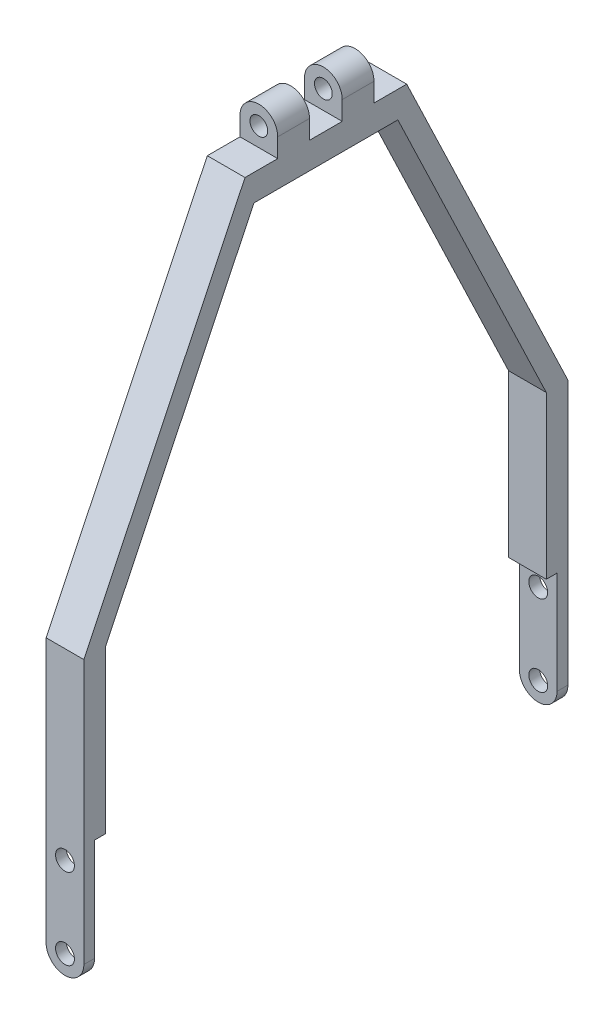
SolidWorks part; units mm, degrees
ref_plane "Front Plane" through (0, 0, 0) normal (0, 0, 1) x (1, 0, 0)
ref_plane "Top Plane" through (0, 0, 0) normal (0, 1, 0) x (1, 0, 0)
ref_plane "Right Plane" through (0, 0, 0) normal (1, 0, 0) x (0, 0, -1)
sketch "Croquis1" plane through (0, 0, 0) normal (0, 0, 1) x (1, 0, 0)
  line L10 (-3.5, 100) -> (-3.5, -15)
  line L11 (3.5, -15) -> (3.5, 100)
  circle A18 centre (0, 0) radius 1.75
  circle A19 centre (0, -15) radius 1.75
  arc A20 (-3.5, -15) -> (3.5, -15) centre (0, -15) ccw
  arc A22 (3.5, 100) -> (-3.5, 100) centre (0, 100) ccw
  circle A23 centre (0, 100) radius 1.65
  dimension "D3" = 3.5
  dimension "D4" = 7
  dimension "D6" = 7
  dimension "D7" = 3.3
  dimension "D2" = 3.5
  dimension "D1" = 15
  dimension "D5" = 100
extrude "Saliente-Extruir1" add sketch "Croquis1" against normal blind 89.8
sketch "Croquis2" plane through (3.5, 0, 0) normal (1, 0, 0) x (0, 0, -1)
  line L0 (0, -18.5) -> (89.8, -18.5) construction
  line L1 (2, -18.5) -> (87.8, -18.5)
  line L2 (2, -18.5) -> (2, 4)
  line L3 (2, 4) -> (87.8, 4)
  line L4 (87.8, -18.5) -> (87.8, 4)
  line L5 (89.8, -15) -> (89.8, 100) construction
  line L6 (29.9, 103.5) -> (0, 103.5)
  line L7 (0, -15) -> (0, 100) construction
  line L8 (4, 4) -> (85.8, 4)
  line L9 (4, 4) -> (4, 34)
  line L10 (4, 34) -> (85.8, 34)
  line L11 (85.8, 4) -> (85.8, 34)
  line L12 (89.8, -15) -> (89.8, 100) construction
  line L13 (44.9, 103.5) -> (44.9, 34) construction
  line L14 (85.8, 34) -> (58.2532, 91.5811)
  line L15 (0, 103.5) -> (0, 34)
  line L16 (89.8, 103.5) -> (0, 103.5) construction
  line L17 (89.8, 100) -> (0, 100) construction
  line L18 (89.8, 34) -> (89.8, 103.5)
  line L19 (89.8, 100) -> (89.8, 103.5) construction
  line L20 (89.8, 103.5) -> (59.9, 103.5)
  line L21 (59.9, 103.5) -> (59.9, 96.5)
  line L22 (59.9, 96.5) -> (89.8, 34)
  line L23 (0, 34) -> (29.9, 96.5)
  line L24 (29.9, 96.5) -> (29.9, 103.5)
  line L25 (0, 103.5) -> (0, 100) construction
  line L26 (4, 34) -> (31.5468, 91.5811)
  line L27 (31.5468, 91.5811) -> (58.2532, 91.5811)
  line L29 (29.9, 103.5) -> (35.97, 103.5)
  line L30 (29.9, 103.5) -> (29.9, 96.5)
  line L31 (29.9, 96.5) -> (35.97, 96.5)
  line L32 (35.97, 103.5) -> (35.97, 96.5)
  line L33 (59.9, 96.5) -> (53.83, 96.5)
  line L34 (59.9, 96.5) -> (59.9, 103.5)
  line L35 (59.9, 103.5) -> (53.83, 103.5)
  line L36 (53.83, 96.5) -> (53.83, 103.5)
  line L37 (47.935, 103.5) -> (41.865, 103.5)
  line L38 (47.935, 103.5) -> (47.935, 96.5)
  line L39 (47.935, 96.5) -> (41.865, 96.5)
  line L40 (41.865, 103.5) -> (41.865, 96.5)
  line L41 (0, -15) -> (0, 100) construction
  point P24 (44.9, 100)
  point P50 (44.9, 103.5)
  dimension "D2" = 30
  dimension "D3" = 4
  dimension "D4" = 4
  dimension "D5" = 15
  dimension "D6" = 7
  dimension "D7" = 4.9189
  dimension "D8" = 7
  dimension "D9" = 15
  dimension "D10" = 6.07
  dimension "D11" = 4
  dimension "D12" = 2
  dimension "D13" = 2
extrude "Cortar-Extruir1" cut sketch "Croquis2" against normal through all
